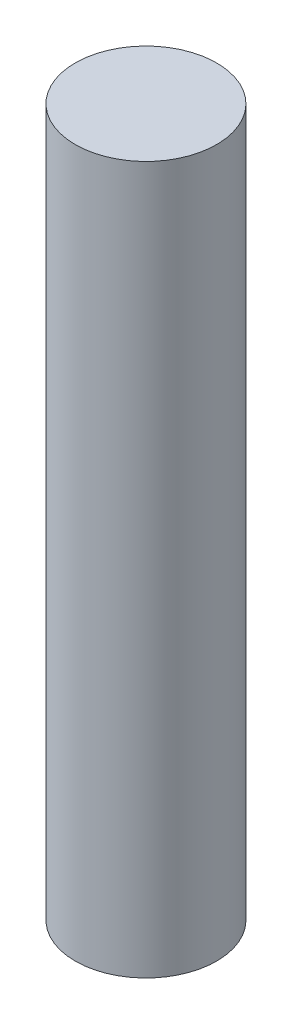
SolidWorks part; units mm, degrees
ref_plane "Front Plane" through (0, 0, 0) normal (0, 0, 1) x (1, 0, 0)
ref_plane "Top Plane" through (0, 0, 0) normal (0, 1, 0) x (1, 0, 0)
ref_plane "Right Plane" through (0, 0, 0) normal (1, 0, 0) x (0, 0, -1)
sketch "Sketch1" plane through (0, 0, 0) normal (0, 1, 0) x (1, 0, 0)
  circle A0 centre (0, 0) radius 20
  dimension "D1" = 40
extrude "Boss-Extrude1" add sketch "Sketch1" along normal blind 200
